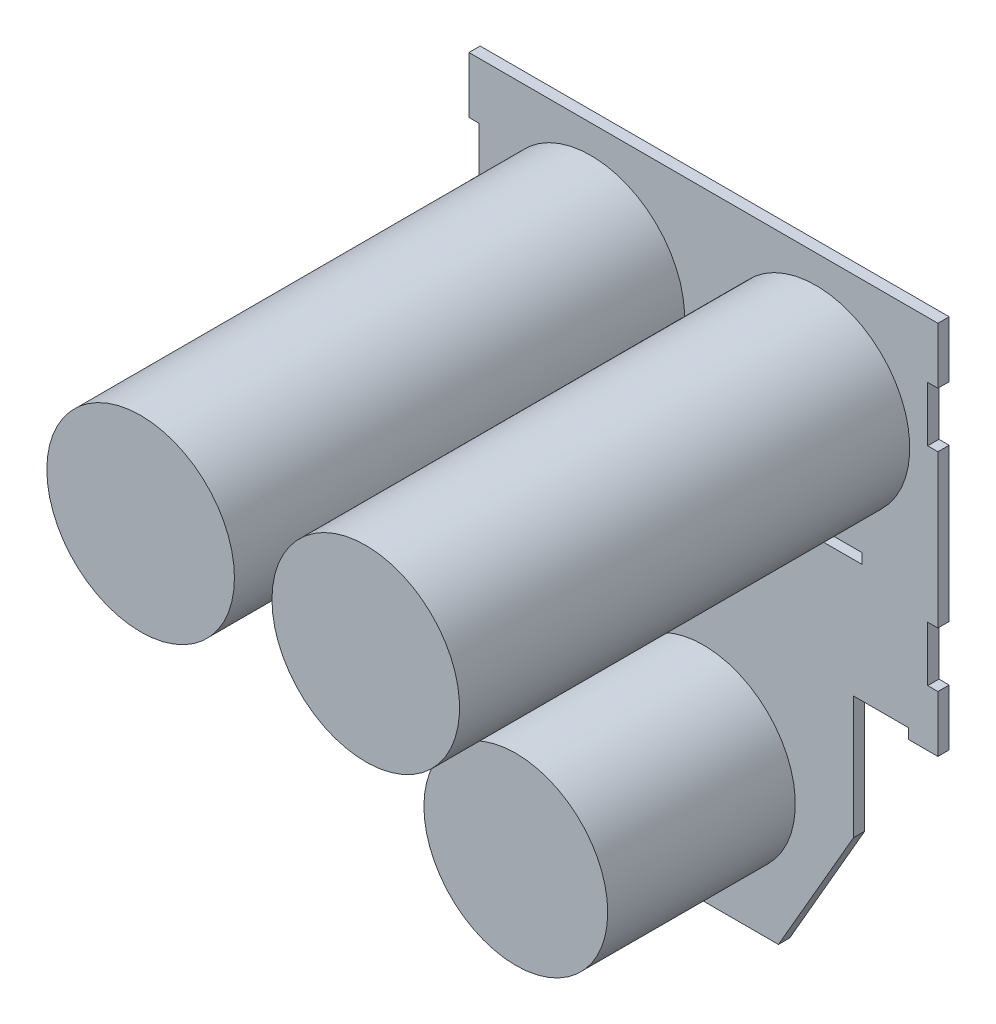
SolidWorks part; units mm, degrees
ref_plane "Спереди" through (0, 0, 0) normal (0, 0, 1) x (1, 0, 0)
ref_plane "Сверху" through (0, 0, 0) normal (0, 1, 0) x (1, 0, 0)
ref_plane "Справа" through (0, 0, 0) normal (1, 0, 0) x (0, 0, -1)
other "Configuration Table"
sketch "Эскиз1" plane through (0, 0, 0) normal (0, 0, 1) x (1, 0, 0)
  line L0 (-125, 0) -> (-125, -260) construction
  line L1 (0, 0) -> (-250, 0)
  line L2 (0, 0) -> (0, -30)
  line L3 (0, -200) -> (-15.7, -200)
  line L4 (-250, 0) -> (-250, -30)
  line L5 (-15, -115) -> (-115, -115) construction
  line L6 (-235, -15) -> (-135, -15) construction
  line L7 (-235, -15) -> (-235, -115) construction
  line L8 (-235, -115) -> (-135, -115) construction
  line L9 (-135, -15) -> (-135, -115) construction
  line L10 (-115, -15) -> (-115, -115) construction
  line L11 (-15, -15) -> (-115, -15) construction
  line L12 (-15, -15) -> (-15, -115) construction
  line L13 (-234.3, -200) -> (-250, -200)
  line L14 (-165, -329.282) -> (-85, -329.282)
  line L15 (-85, -329.282) -> (-45, -260)
  line L19 (-205, -260) -> (-165, -329.282)
  line L20 (-145.7371, -157.3536) -> (-165.7371, -191.9946) [skipped]
  line L21 (-85, -190.718) -> (-125, -190.718) [skipped]
  line L22 (-64.2629, -226.6357) -> (-84.2629, -191.9946) [skipped]
  line L23 (0, -170) -> (-5.45, -170)
  line L24 (-250, -30) -> (-244.55, -30)
  line L26 (-250, -59.3) -> (-244.55, -59.3)
  line L27 (-244.55, -30) -> (-244.55, -59.3)
  line L28 (-250, -140.7) -> (-244.55, -140.7)
  line L30 (-250, -170) -> (-244.55, -170)
  line L31 (-244.55, -140.7) -> (-244.55, -170)
  line L32 (-5.45, -140.7) -> (-5.45, -170)
  line L33 (0, -140.7) -> (-5.45, -140.7)
  line L35 (0, -59.3) -> (-5.45, -59.3)
  line L36 (-5.45, -30) -> (-5.45, -59.3)
  line L37 (0, -30) -> (-5.45, -30)
  line L51 (0, -59.3) -> (0, -140.7)
  line L52 (0, -170) -> (0, -200)
  line L53 (-250, -170) -> (-250, -200)
  line L54 (-250, -59.3) -> (-250, -140.7)
  line L55 (-45, -194.55) -> (-15.7, -194.55)
  line L57 (-205, -260) -> (-205, -194.55)
  line L58 (-205, -194.55) -> (-234.3, -194.55)
  line L59 (-234.3, -200) -> (-234.3, -194.55)
  line L60 (-15.7, -200) -> (-15.7, -194.55)
  line L62 (-45, -260) -> (-45, -194.55)
  line L63 (-40.35, -126.1) -> (-69.65, -126.1)
  line L64 (-209.65, -131.55) -> (-180.35, -131.55)
  line L65 (-209.65, -131.55) -> (-209.65, -126.1)
  line L66 (-209.65, -126.1) -> (-180.35, -126.1)
  line L67 (-180.35, -131.55) -> (-180.35, -126.1)
  line L68 (-139.65, -131.55) -> (-110.35, -131.55)
  line L69 (-139.65, -131.55) -> (-139.65, -126.1)
  line L70 (-139.65, -126.1) -> (-110.35, -126.1)
  line L71 (-110.35, -131.55) -> (-110.35, -126.1)
  line L72 (-69.65, -131.55) -> (-69.65, -126.1)
  line L73 (-40.35, -131.55) -> (-69.65, -131.55)
  line L74 (-40.35, -131.55) -> (-40.35, -126.1)
  dimension "D1" = 250
  dimension "D2" = 200
  dimension "D3" = 100
  dimension "D4" = 15
  dimension "D5" = 15
  dimension "D6" = 80
  dimension "D7" = 29.3
  dimension "D8" = 29.3
  dimension "D9" = 5.45
  dimension "D10" = 30
  dimension "D11" = 30
  dimension "D12" = 29.3
  dimension "D13" = 5.45
  dimension "D14" = 15.7
  dimension "D15" = 160
  dimension "D16" = 29.3
  dimension "D17" = 5.45
  dimension "D18" = 63
  dimension "D19" = 40.7
  dimension "D20" = 239.1
  dimension "D21" = 40.7
  dimension "D22" = 60
extrude "Бобышка-Вытянуть1" add sketch "Эскиз1" along normal blind 6
sketch "Эскиз2" plane through (0, 0, 6) normal (0, 0, 1) x (1, 0, 0)
  line L1 (-165, -329.282) -> (-85, -329.282) construction
  line L2 (-85, -329.282) -> (-45, -260) construction
  line L3 (-45, -260) -> (-85, -190.718) construction
  line L4 (-85, -190.718) -> (-165, -190.718) construction
  line L5 (-165, -190.718) -> (-205, -260) construction
  line L6 (-205, -260) -> (-165, -329.282) construction
  line L7 (-76.0102, -308.9898) -> (-173.9898, -308.9898) construction
  line L8 (-76.0102, -308.9898) -> (-76.0102, -211.0102) construction
  line L9 (-76.0102, -211.0102) -> (-173.9898, -211.0102) construction
  line L10 (-173.9898, -308.9898) -> (-173.9898, -211.0102) construction
  line L11 (-76.0102, -308.9898) -> (-173.9898, -211.0102) construction
  line L12 (-76.0102, -211.0102) -> (-173.9898, -308.9898) construction
  circle A0 centre (-125, -260) radius 69.282 construction
  circle A1 centre (-125, -260) radius 48.9898
  point P1 (-125, -260)
extrude "Бобышка-Вытянуть2" add sketch "Эскиз2" along normal blind 100
sketch "Эскиз3" plane through (0, 0, 6) normal (0, 0, 1) x (1, 0, 0)
  line L0 (-125, 0) -> (-125, -329.282) construction
  line L1 (0, 0) -> (-250, 0) construction
  line L2 (-165, -329.282) -> (-85, -329.282) construction
  line L3 (-250, -59.3) -> (-250, -140.7) construction
  line L4 (-235, -15) -> (-135, -15) construction
  line L5 (-235, -15) -> (-235, -115) construction
  line L6 (-235, -115) -> (-135, -115) construction
  line L7 (-135, -15) -> (-135, -115) construction
  line L8 (-115, -15) -> (-115, -115) construction
  line L9 (-15, -115) -> (-115, -115) construction
  line L10 (-15, -15) -> (-15, -115) construction
  line L11 (-15, -15) -> (-115, -15) construction
  line L12 (-235, -15) -> (-135, -115) construction
  line L13 (-135, -15) -> (-235, -115) construction
  circle A0 centre (-185, -65) radius 50
  circle A1 centre (-65, -65) radius 50
  dimension "D1" = 100
  dimension "D2" = 15
  dimension "D3" = 15
extrude "Бобышка-Вытянуть3" add sketch "Эскиз3" along normal blind 240
